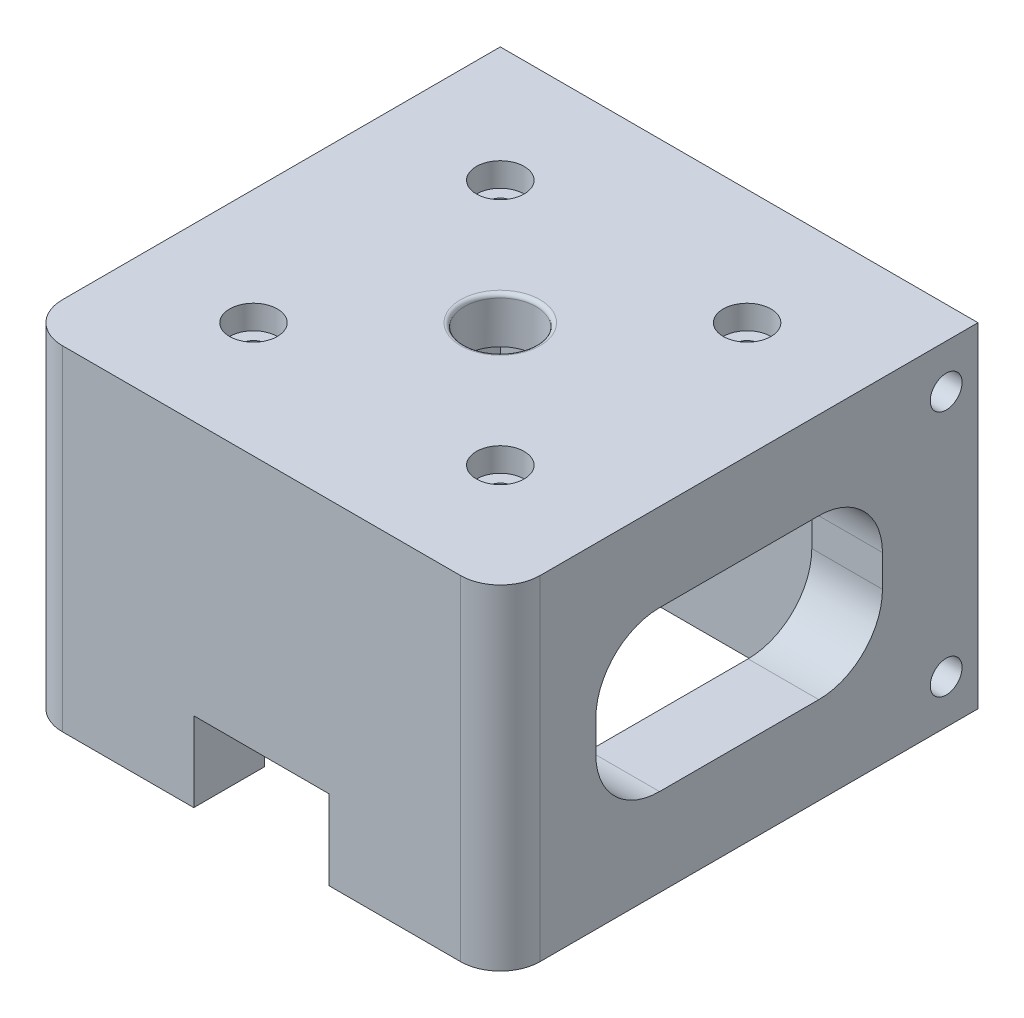
SolidWorks part; units mm, degrees
material "ABS"
ref_plane "Front Plane" through (0, 0, 0) normal (0, 0, 1) x (1, 0, 0)
ref_plane "Top Plane" through (0, 0, 0) normal (0, 1, 0) x (1, 0, 0)
ref_plane "Right Plane" through (0, 0, 0) normal (1, 0, 0) x (0, 0, -1)
other "Configuration Table"
sketch "Sketch1" plane through (0, 0, 0) normal (0, 1, 0) x (1, 0, 0)
  line L1 (30, -30) -> (-30, -30)
  line L2 (30, -30) -> (30, 30)
  line L3 (30, 30) -> (-30, 30)
  line L4 (-30, -30) -> (-30, 30)
  line L5 (30, -30) -> (-30, 30) construction
  line L6 (30, 30) -> (-30, -30) construction
  point P0 (0, 0)
  dimension "D1" = 60
extrude "Boss-Extrude1" add sketch "Sketch1" along normal blind 8
sketch "Sketch2" plane through (0, 8, 0) normal (0, 1, 0) x (1, 0, 0)
  circle A0 centre (0, 0) radius 4.5
  dimension "D1" = 9
extrude "Cut-Extrude1" cut sketch "Sketch2" against normal blind 8
sketch "Sketch3" plane through (0, 0, 0) normal (0, -1, 0) x (1, 0, 0)
  circle A0 centre (0, 0) radius 11
  dimension "D1" = 22
extrude "Cut-Extrude2" cut sketch "Sketch3" against normal blind 2.2
sketch "Sketch4" plane through (0, 0, 0) normal (0, -1, 0) x (1, 0, 0)
  line L1 (15.5, -15.5) -> (-15.5, -15.5) construction
  line L2 (15.5, -15.5) -> (15.5, 15.5) construction
  line L3 (15.5, 15.5) -> (-15.5, 15.5) construction
  line L4 (-15.5, -15.5) -> (-15.5, 15.5) construction
  line L5 (15.5, -15.5) -> (-15.5, 15.5) construction
  line L6 (15.5, 15.5) -> (-15.5, -15.5) construction
  circle A0 centre (-15.5, 15.5) radius 1.5
  circle A1 centre (-15.5, -15.5) radius 1.5
  circle A2 centre (15.5, -15.5) radius 1.5
  circle A3 centre (15.5, 15.5) radius 1.5
  point P0 (0, 0)
  dimension "D2" = 3
  dimension "D3" = 3
  dimension "D4" = 3
  dimension "D5" = 3
  dimension "D1" = 31
extrude "Cut-Extrude3" cut sketch "Sketch4" against normal blind 11.2
sketch "Sketch6" plane through (0, 8, 0) normal (0, 1, 0) x (1, 0, 0)
  circle A1 centre (-15.5, 15.5) radius 3
  circle A2 centre (15.5, 15.5) radius 3
  circle A3 centre (-15.5, -15.5) radius 3
  circle A4 centre (15.5, -15.5) radius 3
  dimension "D1" = 6
  dimension "D2" = 6
  dimension "D3" = 6
  dimension "D4" = 6
extrude "Cut-Extrude4" cut sketch "Sketch6" against normal blind 3
sketch "Sketch7" plane through (0, 0, 0) normal (0, -1, 0) x (1, 0, 0)
  line L19 (21.125, -21.125) -> (-21.125, -21.125) construction
  line L20 (21.125, -21.125) -> (21.125, 21.125) construction
  line L21 (21.125, 21.125) -> (-21.125, 21.125) construction
  line L22 (-21.125, -21.125) -> (-21.125, 21.125) construction
  line L23 (21.125, -21.125) -> (-21.125, 21.125) construction
  line L24 (21.125, 21.125) -> (-21.125, -21.125) construction
  line L26 (-30, -30) -> (-30, 30)
  line L27 (-30, 30) -> (30, 30)
  line L28 (30, 30) -> (30, -30)
  line L29 (30, -30) -> (-30, -30)
  line L30 (-21.125, -21.125) -> (-21.125, 21.125)
  line L31 (-21.125, 21.125) -> (21.125, 21.125)
  line L32 (21.125, 21.125) -> (21.125, -21.125)
  line L33 (21.125, -21.125) -> (-21.125, -21.125)
  point P0 (0, 0)
  dimension "D1" = 42.25
extrude "Boss-Extrude3" add sketch "Sketch7" along normal blind 34
sketch "Sketch8" plane through (0, -34, 0) normal (0, -1, 0) x (1, 0, 0)
  line L0 (30, 21.12) -> (-30, 21.12) construction
  line L2 (-30, 30) -> (-30, -30) construction
  line L3 (-30, 21.12) -> (30, 30) construction
  line L4 (-30, 30) -> (30, 21.12) construction
  line L5 (30, 25.56) -> (-30, 25.56) construction
  line L6 (30, 30) -> (-30, 30) construction
  line L7 (-8.5, 21.12) -> (8.5, 21.12)
  line L8 (-8.5, 21.12) -> (-8.5, 30)
  line L9 (-8.5, 30) -> (8.5, 30)
  line L10 (8.5, 21.12) -> (8.5, 30)
  line L11 (-8.5, 21.12) -> (8.5, 30) construction
  line L12 (-8.5, 30) -> (8.5, 21.12) construction
  point P5 (0, 21.12)
  point P9 (0, 25.56)
  point P16 (0, 25.56)
  dimension "D1" = 17
  dimension "D2" = 8.88
extrude "Cut-Extrude5" cut sketch "Sketch8" against normal blind 10
sketch "Sketch9" plane through (30, 0, 0) normal (1, 0, 0) x (0, 0, -1)
  line L0 (-30, -34) -> (30, 8) construction
  line L1 (-30, 8) -> (30, -34) construction
  line L3 (18, -23) -> (-18, -23)
  line L4 (18, -23) -> (18, -3)
  line L5 (18, -3) -> (-18, -3)
  line L6 (-18, -23) -> (-18, -3)
  line L7 (18, -23) -> (-18, -3) construction
  line L8 (18, -3) -> (-18, -23) construction
  point P8 (0, -13)
  dimension "D1" = 20
  dimension "D2" = 36
extrude "Cut-Extrude6" cut sketch "Sketch9" against normal blind 60
fillet "Fillet1" radius 0.5 1 edges at (0, 8, 4.5)
fillet "Fillet2" radius 8 8 edges at (-25.5625, -23, -18) (-25.5625, -3, -18) (-25.5625, -23, 18) (-25.5625, -3, 18) (25.5625, -23, -18) (25.5625, -3, -18) (25.5625, -23, 18) (25.5625, -3, 18)
fillet "Fillet3" radius 5 2 edges at (-30, -13, 30) (30, -13, 30)
sketch "Sketch10" plane through (30, 0, 0) normal (1, 0, 0) x (0, 0, -1)
  circle A0 centre (26, -28.5) radius 2
  circle A1 centre (26, 2.5) radius 2
  dimension "D1" = 4
  dimension "D2" = 4
extrude "Cut-Extrude7" cut sketch "Sketch10" against normal blind 14
sketch "Sketch11" plane through (-30, 0, 0) normal (-1, 0, 0) x (0, 0, 1)
  circle A0 centre (-26, 2.5) radius 2
  circle A1 centre (-26, -28.5) radius 2
  dimension "D1" = 4
  dimension "D2" = 4
extrude "Cut-Extrude8" cut sketch "Sketch11" against normal blind 14
